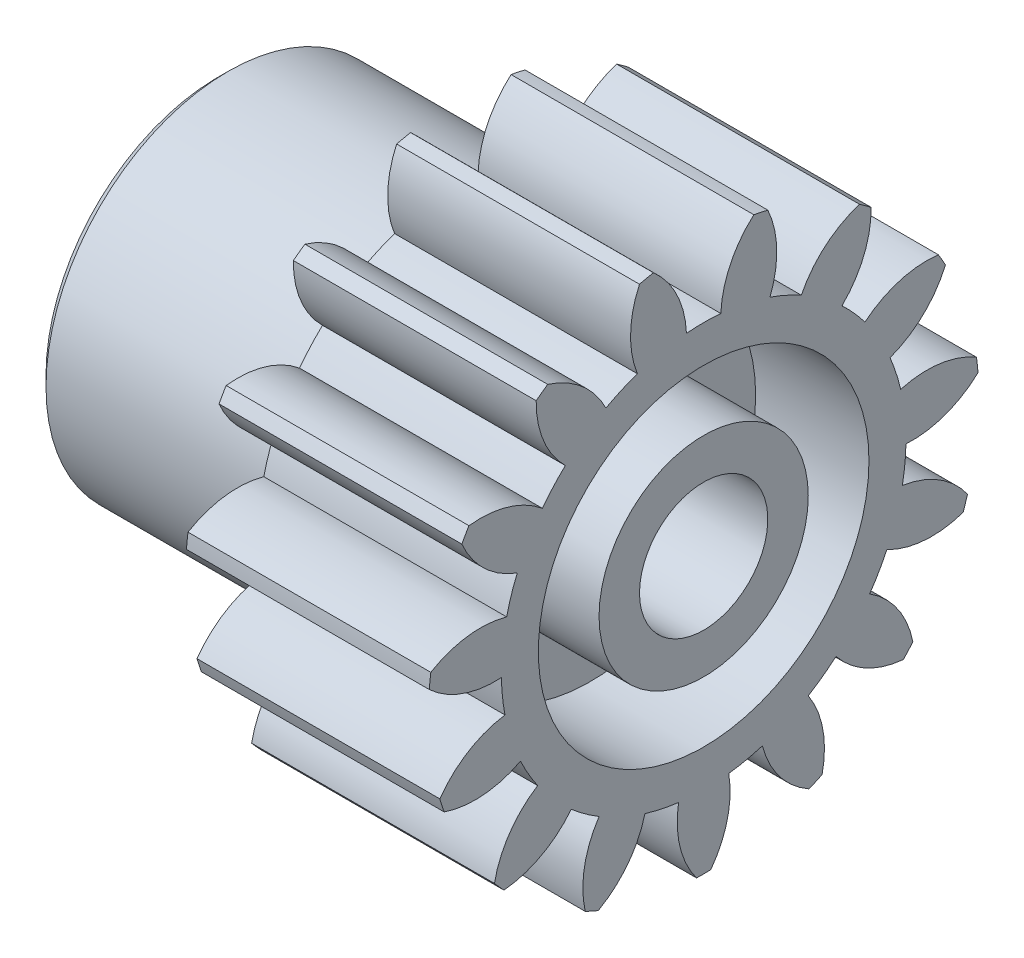
SolidWorks part; units mm, degrees
ref_plane "Plane1" through (0, 0, 0) normal (0, 0, 1) x (1, 0, 0)
ref_plane "Plane2" through (0, 0, 0) normal (0, 1, 0) x (1, 0, 0)
ref_plane "Plane3" through (0, 0, 0) normal (1, 0, 0) x (0, 0, -1)
sketch "HoldingSke" plane through (0, 0, 0) normal (0, 1, 0) x (1, 0, 0)
  line L0 (0, 0) -> (1.2074, -0.3235)
  line L1 (-15, 0) -> (100, 0) construction
  line L2 (0, 0) -> (-2.1039, 2.3779)
  line L3 (0, 0) -> (-11.863, 4.5341)
  line L4 (0, 0) -> (8.3417, 2.2352)
  line L5 (0, 0) -> (-46.8476, -17.4728)
  line L6 (0, 0) -> (-4.9738, -3.3558)
  line L7 (-2.1039, 2.3779) -> (8.6586, 51.2059)
  line L8 (-76.2, 54.61) -> (-76.1, 54.61)
  line L9 (-71.009, 38.7566) -> (-53.1078, 45.2721)
  line L10 (-76.2, 71.12) -> (104.1128, 71.12)
  line L11 (0, 0) -> (-6, 0)
  line L12 (-76.2, 101.6) -> (-76.17, 101.6)
  line L13 (24.9733, 27.94) -> (52.9518, 28.4284)
  line L14 (24.9733, 27.94) -> (24.9743, 27.94)
  line L15 (24.9733, 27.94) -> (100.4006, 29.5858)
  line L16 (-63.627, -0.8) -> (-12.827, -0.8)
  circle A0 centre (0, 0) radius 0.4
  circle A1 centre (0, 0) radius 4.999
  circle A2 centre (0, 0) radius 37.5
  circle A3 centre (0, 0) radius 0.4
  dimension "MHD" = 9.998
  dimension "Hub_dia" = 75
  dimension "Bore" = 0.8
  dimension "MBD" = 0.8
  dimension "Num_teeth" = 15
  dimension "Pitch" = 1.25
  dimension "Overall_len" = 50
  dimension "Show_teeth" = 15
  dimension "Thickness" = 6
  dimension "OAL" = 50.0001
  dimension "T_dim" = 0.1
  dimension "Ap" = 20
  dimension "H" = 19.05
  dimension "Pitch_radius" = 180.3128
  dimension "Width" = 6
  dimension "Backlash" = 0.03
  dimension "Addendum_fac" = 1
  dimension "Dedendum_fac" = 1.25
  dimension "Clearance_fac" = 0.25
  dimension "Dedendum_add" = 0.001
  dimension "Module" = 0.8
sketch "BasProSke" plane through (0, 0, 0) normal (0, 1, 0) x (1, 0, 0)
  line L0 (-10, 0) -> (60, 0) construction
  line L1 (0, 0) -> (0, 6.8)
  line L2 (0, 0) -> (6, 0)
  line L3 (6, 0) -> (6, 6.8)
  line L4 (6, 6.8) -> (0, 6.8)
  dimension "Thickness" = 6
  dimension "Diameter" = 13.6
revolve "Base-Revolve" add sketch "BasProSke" angle 360 about L0
sketch "TooCutSke" plane through (0, 0, 0) normal (1, 0, 0) x (0, 0, -1)
  line L1 (0, 0) -> (0, 107) construction
  line L2 (0, 0) -> (-0.6796, 5.9614) construction
  line L3 (0, 0) -> (-2.4835, 11.6838) construction
  line L4 (-0.6796, 5.9614) -> (-1.2417, 5.8419) construction
  arc A0 (0.4247, 4.9809) -> (-0.4247, 4.9809) centre (0, 0) ccw
  arc A1 (1.2655, 6.7071) -> (-1.2655, 6.7071) centre (0, 0) ccw
  circle A2 centre (0, 0) radius 6 construction
  circle A3 centre (0, 0) radius 5.6382 construction
  arc A4 (-0.4247, 4.9809) -> (-1.2655, 6.7071) centre (-2.8226, 4.8808) ccw
  arc A5 (1.2655, 6.7071) -> (0.4247, 4.9809) centre (2.8226, 4.8808) ccw
  dimension "Root_dia" = 9.998
  dimension "Overcut_dia" = 13.6508
  dimension "Pitch_dia" = 12
  dimension "Base_dia" = 11.2763
  dimension "Flank_rad" = 2.4
  dimension "Half_ang" = 12
  dimension "Half_CT" = 0.5747
extrude "ToothCut" cut sketch "TooCutSke" along normal through all
fillet "Breaks" [suppressed] radius 0.016
fillet "RootFillets" [suppressed] radius 0.201
pattern_circular "TeethCuts" count 15 every 24 about axis through (-10, 0, 0) along (1, 0, 0) of "ToothCut", "RootFillets", "Breaks"
sketch "HubNeaOneSke" plane through (0, 0, 0) normal (-1, 0, 0) x (0, 0, 1)
  circle A0 centre (0, 0) radius 4.999
  dimension "Diameter" = 9.998
extrude "HubNearOne" [suppressed] add sketch "HubNeaOneSke" along normal blind 44.0001
sketch "HubNeaBotSke" plane through (0, 0, 0) normal (-1, 0, 0) x (0, 0, 1)
  circle A0 centre (0, 0) radius 4.999
  dimension "Diameter" = 9.998
extrude "HubNearBoth" [suppressed] add sketch "HubNeaBotSke" along normal blind 22
ref_plane "FarPln" through (6, 0, 0) normal (1, 0, 0) x (0, 0, -1)
sketch "HubFarSke" plane through (6, 0, 0) normal (1, 0, 0) x (0, 0, -1)
  circle A0 centre (0, 0) radius 4.999
  dimension "Diameter" = 9.998
extrude "HubFar" [suppressed] add sketch "HubFarSke" along normal blind 22
sketch "BorSke" plane through (0, 0, 0) normal (1, 0, 0) x (0, 0, -1)
  circle A0 centre (0, 0) radius 0.4
  dimension "Diameter" = 0.8
extrude "Bore" cut sketch "BorSke" along normal mid plane 100.0001
sketch "KeySke" plane through (0, 0, 0) normal (1, 0, 0) x (0, 0, -1)
  line L0 (-0.05, 0) -> (-0.05, 0.5)
  line L1 (-0.05, 0.5) -> (0.05, 0.5)
  line L2 (0.05, 0.5) -> (0.05, 0)
  line L3 (0, 0) -> (0, 34) construction
  line L4 (-0.05, 0) -> (0.05, 0)
  dimension "Offset" = 0.5
  dimension "Width" = 0.1
extrude "Keyway" [suppressed] cut sketch "KeySke" along normal mid plane 100.0001
pattern_circular "Keyway2" [suppressed] count 2 every 90 about axis through (-10, 0, 0) along (1, 0, 0)
sketch "Esquisse1" plane through (0, 0, 0) normal (-1, 0, 0) x (0, 0, 1)
  circle A0 centre (0, 0) radius 4.5
  dimension "D1" = 9
extrude "Boss.-Extru.1" add sketch "Esquisse1" along normal blind 6
sketch "Esquisse2" plane through (-6, 0, 0) normal (-1, 0, 0) x (0, 0, 1)
  circle A0 centre (0, 0) radius 1.585
  dimension "D1" = 3.17
extrude "Enlèv. mat.-Extru.1" cut sketch "Esquisse2" against normal up to next
sketch "Esquisse3" plane through (6, 0, 0) normal (1, 0, 0) x (0, 0, -1)
  circle A0 centre (0, 0) radius 2.585
  circle A1 centre (0, 0) radius 1.585 construction
  circle A2 centre (0, 0) radius 4.085
  dimension "D1" = 1
  dimension "D2" = 1.5
extrude "Enlèv. mat.-Extru.2" cut sketch "Esquisse3" against normal blind 2.8
chamfer "Chanfrein1" distance 0.25 angle 45 1 edges at (-6, 0, 4.5)
equation "' \"Module@HoldingSke\" = 6.35"
equation "' \"Num_teeth@HoldingSke\" = 12"
equation "' \"Ap@HoldingSke\" =  20"
equation "' \"Ap@HoldingSke\" = 20"
equation "' \"Width@HoldingSke\" = 0.5 * 25.4"
equation "' \"Hub_dia@HoldingSke\"= 1 * 25.4"
equation "' \"Hub_dia@HoldingSke\" = 1 * 25.4"
equation "' \"Overall_len@HoldingSke\" = 1.0 * 25.4"
equation "' \"Bore@HoldingSke\" = 0.75 * 25.4"
equation "' \"T_dim@HoldingSke\" = 0.1 * 25.4"
equation "' \"Width@KeySke\" = 0.25 * 25.4"
equation "' \"Show_teeth@HoldingSke\" = 13"
equation "' \"Backlash@HoldingSke\" = 0.009 * 25.4"
equation "' \"Addendum_fac@HoldingSke\" = 1.0"
equation "' \"Dedendum_fac@HoldingSke\" = 1.25"
equation "' \"Dedendum_add@HoldingSke\" = 0.00005 * 25.4"
equation "' \"Clearance_fac@HoldingSke\" = 0.25"
equation "\"Pitch@HoldingSke\" = 1 / \"Module@HoldingSke\""
equation "\"Overcut_dia@TooCutSke\" = (\"Num_teeth@HoldingSke\" + 2 * \"Addendum_fac@HoldingSke\") / \"Pitch@HoldingSke\" + 0.002 * 25.4"
equation "\"Pitch_dia@TooCutSke\" = \"Num_teeth@HoldingSke\" / \"Pitch@HoldingSke\""
equation "\"Base_dia@TooCutSke\" = \"Num_teeth@HoldingSke\" / \"Pitch@HoldingSke\" * cos((\"Ap@HoldingSke\"  * 3.14159265 / 180))"
equation "\"Root_dia@TooCutSke\" = (\"Num_teeth@HoldingSke\" + 2) / \"Pitch@HoldingSke\" - 2 * (\"Addendum_fac@HoldingSke\" + \"Dedendum_fac@HoldingSke\") / \"Pitch@HoldingSke\" - \"Dedendum_add@HoldingSke\" * 2"
equation "\"Half_ang@TooCutSke\" = 180 / \"Num_teeth@HoldingSke\""
equation "\"Half_CT@TooCutSke\" = \"Num_teeth@HoldingSke\" / \"Pitch@HoldingSke\" * sin((3.14159265 / 2 / \"Num_teeth@HoldingSke\")) / 2 - 7 * \"Backlash@HoldingSke\" / 4"
equation "\"Flank_rad@TooCutSke\" = \"Num_teeth@HoldingSke\" / \"Pitch@HoldingSke\" / 5"
equation "\"Radius@RootFillets\" = \"Clearance_fac@HoldingSke\" / \"Pitch@HoldingSke\" + \"Dedendum_add@HoldingSke\""
equation "\"Break_rad@Breaks\" = 0.02 / \"Pitch@HoldingSke\""
equation "\"Thickness@HoldingSke\" = \"Width@HoldingSke\""
equation "\"OAL@HoldingSke\" = \"Thickness@HoldingSke\""
equation "\"MHD@HoldingSke\" = (\"Num_teeth@HoldingSke\" + 2) / \"Pitch@HoldingSke\" - 2 * (\"Addendum_fac@HoldingSke\" + \"Dedendum_fac@HoldingSke\")  / \"Pitch@HoldingSke\" - \"Dedendum_add@HoldingSke\" * 2"
equation "\"MBD@HoldingSke\" = (\"Num_teeth@HoldingSke\" + 2) / \"Pitch@HoldingSke\" - 2 * (\"Addendum_fac@HoldingSke\" + \"Dedendum_fac@HoldingSke\")  / \"Pitch@HoldingSke\" - \"Dedendum_add@HoldingSke\" * 2 - 0.002 * 25.4"
equation "\"MHD@HoldingSke\" = ((sgn( \"MHD@HoldingSke\" - \"Hub_dia@HoldingSke\" )-1)*( \"MHD@HoldingSke\" - \"Hub_dia@HoldingSke\" ))/-2+ \"Hub_dia@HoldingSke\""
equation "\"MBD@HoldingSke\" = ((sgn( \"MBD@HoldingSke\" - \"Bore@HoldingSke\" )-1)*( \"MBD@HoldingSke\" - \"Bore@HoldingSke\" ))/-2+ \"Bore@HoldingSke\""
equation "\"OAL@HoldingSke\" = ((sgn( \"OAL@HoldingSke\" - \"Overall_len@HoldingSke\" )+1)*( \"OAL@HoldingSke\" - \"Overall_len@HoldingSke\" ))/2 + \"Overall_len@HoldingSke\" + 0.000002 * 25.4"
equation "\"Num_teeth@TeethCuts\" = int( \"Show_teeth@HoldingSke\" ) + 1"
equation "\"Num_teeth@TeethCuts\" = ((sgn( \"Num_teeth@TeethCuts\" - \"Num_teeth@HoldingSke\" )-1)*( \"Num_teeth@TeethCuts\" - \"Num_teeth@HoldingSke\" ))/-2+ \"Num_teeth@HoldingSke\""
equation "\"Num_teeth@TeethCuts\" = ((sgn( \"Num_teeth@TeethCuts\" - 2.0)+1)*( \"Num_teeth@TeethCuts\" - 2.0))/2 +2.0"
equation "\"Angle@TeethCuts\" = 360.0 / \"Num_teeth@HoldingSke\""
equation "\"Diameter@BasProSke\" = (\"Num_teeth@HoldingSke\" + 2 * \"Addendum_fac@HoldingSke\") / \"Pitch@HoldingSke\""
equation "\"Thickness@BasProSke\"  = \"Thickness@HoldingSke\""
equation "' \"Fillet_rad@BasProSke\" =  \"Thickness@HoldingSke\" * 0.05"
equation "' \"Fillet_rad@BasProSke\" = \"Thickness@HoldingSke\" * 0.05"
equation "\"MHD@HoldingSke\" = ((sgn( \"MHD@HoldingSke\" - \"Root_dia@TooCutSke\" )-1)*( \"MHD@HoldingSke\" - \"Root_dia@TooCutSke\" ))/-2+ \"Root_dia@TooCutSke\""
equation "\"Diameter@HubNeaOneSke\" = \"MHD@HoldingSke\""
equation "\"Length@HubNearOne\" = \"OAL@HoldingSke\" - \"Thickness@BasProSke\""
equation "\"Diameter@HubNeaBotSke\" = \"MHD@HoldingSke\""
equation "\"Length@HubNearBoth\" = ( \"OAL@HoldingSke\" - \"Thickness@BasProSke\" ) / 2.0"
equation "\"Thickness@FarPln\" = \"Thickness@BasProSke\""
equation "\"Diameter@HubFarSke\" = \"MHD@HoldingSke\""
equation "\"Length@HubFar\" = ( \"OAL@HoldingSke\" - \"Thickness@BasProSke\" ) / 2.0"
equation "\"Diameter@BorSke\" = \"MBD@HoldingSke\""
equation "\"D1@Bore\" = \"OAL@HoldingSke\" * 2.0"
equation "\"D1@Keyway\" = \"OAL@HoldingSke\" * 2.0"
equation "\"Offset@KeySke\" = \"T_dim@HoldingSke\" + \"MBD@HoldingSke\" / 2.0"
